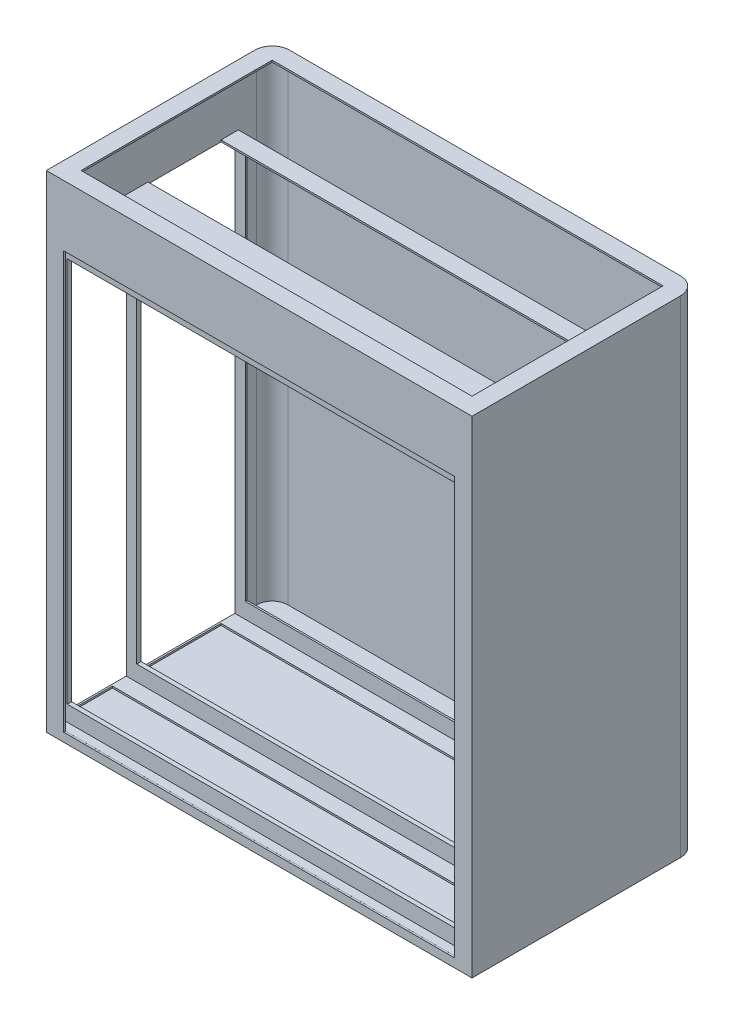
SolidWorks part; units mm, degrees
ref_plane "Front Plane" through (0, 0, 0) normal (0, 0, 1) x (1, 0, 0)
ref_plane "Top Plane" through (0, 0, 0) normal (0, 1, 0) x (1, 0, 0)
ref_plane "Right Plane" through (0, 0, 0) normal (1, 0, 0) x (0, 0, -1)
sketch "Sketch1" plane through (0, 0, 0) normal (0, 1, 0) x (1, 0, 0)
  line L0 (-285.75, 175.26) -> (285.75, 175.26)
  line L1 (-311.15, -152.4) -> (-285.75, -152.4)
  line L2 (-311.15, -152.4) -> (-311.15, 152.4)
  line L3 (-285.75, 177.8) -> (285.75, 177.8)
  line L4 (311.15, -152.4) -> (311.15, 152.4)
  line L5 (-311.15, -177.8) -> (311.15, 177.8) construction
  line L6 (-311.15, 177.8) -> (311.15, -177.8) construction
  line L7 (308.61, -149.86) -> (308.61, 152.4)
  line L8 (-285.75, -152.4) -> (-285.75, -149.86)
  line L9 (-308.61, -149.86) -> (-308.61, 152.4)
  line L10 (-285.75, -149.86) -> (-308.61, -149.86)
  line L11 (311.15, -152.4) -> (285.75, -152.4)
  line L12 (285.75, -152.4) -> (285.75, -149.86)
  line L13 (285.75, -149.86) -> (308.61, -149.86)
  line L14 (-285.75, -177.8) -> (285.75, -177.8) construction
  line L15 (-285.75, -175.26) -> (285.75, -175.26) construction
  line L16 (-308.61, -152.4) -> (-308.61, 152.4) construction
  line L17 (308.61, -152.4) -> (308.61, 152.4) construction
  arc A0 (285.75, -175.26) -> (308.61, -152.4) centre (285.75, -152.4) ccw construction
  arc A2 (285.75, 177.8) -> (311.15, 152.4) centre (285.75, 152.4) cw
  arc A3 (-311.15, 152.4) -> (-285.75, 177.8) centre (-285.75, 152.4) cw
  arc A4 (-308.61, 152.4) -> (-285.75, 175.26) centre (-285.75, 152.4) cw
  arc A5 (285.75, 175.26) -> (308.61, 152.4) centre (285.75, 152.4) cw
  arc A7 (285.75, -177.8) -> (311.15, -152.4) centre (285.75, -152.4) ccw construction
  arc A8 (-285.75, -177.8) -> (-311.15, -152.4) centre (-285.75, -152.4) cw construction
  arc A9 (-285.75, -175.26) -> (-308.61, -152.4) centre (-285.75, -152.4) cw construction
  point P0 (0, 0)
  dimension "D3" = 25.4
  dimension "D1" = 355.6
  dimension "D2" = 622.3
  dimension "D5" = 2.54
  dimension "D6" = 25.4
  dimension "D7" = 2.54
  dimension "D4" = 2.54
extrude "Boss-Extrude1" add sketch "Sketch1" along normal blind 711.2
sketch "Sketch2" plane through (-311.15, 0, 0) normal (-1, 0, 0) x (0, 0, 1)
  line L0 (152.4, 12.7) -> (111.76, 12.7) construction
  line L1 (149.86, 622.3) -> (137.16, 622.3)
  line L2 (-100.33, 12.7) -> (-123.19, 12.7)
  line L3 (149.86, 12.7) -> (137.16, 12.7)
  line L4 (137.16, 622.3) -> (137.16, 599.44)
  line L5 (130.81, 622.3) -> (111.76, 622.3)
  line L6 (130.81, 622.3) -> (130.81, 599.44)
  line L7 (130.81, 12.7) -> (111.76, 12.7)
  line L8 (35.56, 622.3) -> (35.56, 599.44)
  line L9 (29.21, 622.3) -> (6.35, 622.3)
  line L10 (29.21, 622.3) -> (29.21, 599.44)
  line L11 (29.21, 12.7) -> (6.35, 12.7)
  line L12 (-123.19, 622.3) -> (-123.19, 599.44)
  line L13 (152.4, 711.2) -> (152.4, 0) construction
  line L15 (149.86, 0) -> (-152.4, 0) construction
  line L16 (137.16, 10.16) -> (149.86, 10.16)
  line L17 (149.86, 10.16) -> (149.86, 12.7)
  line L18 (-125.73, 599.44) -> (-123.19, 599.44)
  line L19 (-125.73, 624.84) -> (-125.73, 599.44)
  line L20 (-123.19, 317.5) -> (130.81, 317.5) construction
  line L21 (-100.33, 624.84) -> (-125.73, 624.84)
  line L22 (-100.33, 622.3) -> (-100.33, 624.84)
  line L23 (137.16, 10.16) -> (137.16, 12.7)
  line L24 (6.35, 624.84) -> (6.35, 622.3)
  line L25 (58.42, 624.84) -> (6.35, 624.84)
  line L26 (134.0991, 35.56) -> (137.16, 35.56)
  line L27 (134.0991, 35.56) -> (130.81, 35.56)
  line L28 (58.42, 622.3) -> (58.42, 624.84)
  line L29 (29.21, 599.44) -> (35.56, 599.44)
  line L30 (137.16, 10.16) -> (111.76, 10.16)
  line L31 (111.76, 10.16) -> (111.76, 12.7)
  line L32 (58.42, 12.7) -> (58.42, 10.16)
  line L33 (58.42, 10.16) -> (6.35, 10.16)
  line L34 (6.35, 10.16) -> (6.35, 12.7)
  line L35 (-100.33, 12.7) -> (-100.33, 10.16)
  line L36 (29.21, 35.56) -> (35.56, 35.56)
  line L37 (-100.33, 10.16) -> (-125.73, 10.16)
  line L38 (-125.73, 10.16) -> (-125.73, 35.56)
  line L39 (-125.73, 35.56) -> (-123.19, 35.56)
  line L40 (111.76, 624.84) -> (111.76, 622.3)
  line L41 (137.16, 624.84) -> (111.76, 624.84)
  line L42 (137.16, 624.84) -> (149.86, 624.84)
  line L43 (149.86, 624.84) -> (149.86, 622.3)
  line L44 (134.0991, 599.44) -> (137.16, 599.44)
  line L45 (134.0991, 599.44) -> (130.81, 599.44)
  line L46 (-123.19, 35.56) -> (-123.19, 12.7)
  line L47 (-100.33, 622.3) -> (-123.19, 622.3)
  line L48 (29.21, 35.56) -> (29.21, 12.7)
  line L49 (35.56, 35.56) -> (35.56, 12.7)
  line L50 (130.81, 35.56) -> (130.81, 12.7)
  line L51 (137.16, 35.56) -> (137.16, 12.7)
  line L52 (58.42, 622.3) -> (35.56, 622.3)
  line L53 (-100.33, 12.7) -> (-125.73, 12.7) construction
  line L54 (58.42, 12.7) -> (6.35, 12.7) construction
  line L55 (58.42, 12.7) -> (35.56, 12.7)
  point P58 (-91.7591, 55.0071)
  dimension "D4" = 12.7
  dimension "D5" = 95.25
  dimension "D6" = 152.4
  dimension "D7" = 12.7
  dimension "D8" = 6.35
  dimension "D9" = 6.35
  dimension "D11" = 25.4
  dimension "D12" = 2.54
  dimension "D13" = 25.4
  dimension "D14" = 2.54
  dimension "D15" = 22.86
  dimension "D16" = 22.86
  dimension "D17" = 25.4
  dimension "D18" = 25.4
  dimension "D19" = 25.4
  dimension "D20" = 2.54
  dimension "D21" = 2.54
extrude "Boss-Extrude2" add sketch "Sketch2" against normal up to surface (619.76 mm away) contours L47 L22 L21 L19 L18 L12 | L52 L28 L25 L24 L9 L10 L29 L8 | L45 L44 L4 L1 L43 L42 L41 L40 L5 L6 | L46 L39 L38 L37 L35 L2 | L32 L55 L49 L36 L48 L11 L34 L33 | L51 L26 L27 L50 L7 L31 L30 L23 | L23 L16 L17 L3 up to face at (308.61, 355.6, -1.27)
sketch "Sketch3" plane through (-311.15, 0, 0) normal (-1, 0, 0) x (0, 0, 1)
  line L1 (-123.19, 622.3) -> (29.21, 622.3)
  line L2 (-123.19, 622.3) -> (-123.19, 12.7)
  line L3 (-123.19, 12.7) -> (29.21, 12.7)
  line L4 (29.21, 622.3) -> (29.21, 12.7)
  line L5 (35.56, 12.7) -> (130.81, 12.7)
  line L6 (35.56, 12.7) -> (35.56, 622.3)
  line L7 (35.56, 622.3) -> (130.81, 622.3)
  line L8 (130.81, 12.7) -> (130.81, 622.3)
  line L9 (137.16, 622.3) -> (149.86, 622.3)
  line L10 (137.16, 622.3) -> (137.16, 12.7)
  line L11 (137.16, 12.7) -> (149.86, 12.7)
  line L12 (149.86, 622.3) -> (149.86, 12.7)
extrude "Cut-Extrude1" cut sketch "Sketch3" against normal blind 2.54
sketch "Sketch4" plane through (0, 624.84, 0) normal (0, 1, 0) x (1, 0, 0)
  line L0 (-308.61, -29.21) -> (-308.61, -35.56) construction
  line L1 (-308.61, -130.81) -> (-308.61, -137.16) construction
  line L2 (-308.61, 125.73) -> (-308.61, 123.19) construction
  line L3 (-308.61, -29.21) -> (-308.61, -35.56)
  line L4 (-308.61, -130.81) -> (-308.61, -137.16)
  line L5 (-308.61, 125.73) -> (-308.61, 123.19)
  line L6 (-308.61, 123.19) -> (-295.91, 123.19)
  line L7 (-295.91, 123.19) -> (-295.91, 125.73)
  line L8 (308.61, 125.73) -> (-308.61, 125.73) construction
  line L9 (-295.91, 125.73) -> (-308.61, 125.73)
  line L10 (-308.61, -29.21) -> (-295.91, -29.21)
  line L11 (-295.91, -29.21) -> (-295.91, -35.56)
  line L12 (-295.91, -35.56) -> (-308.61, -35.56)
  line L13 (-308.61, -130.81) -> (-295.91, -130.81)
  line L14 (-295.91, -130.81) -> (-295.91, -137.16)
  line L15 (-295.91, -137.16) -> (-308.61, -137.16)
  line L16 (0, 0) -> (0, 245.9045) construction
  line L17 (295.91, -137.16) -> (308.61, -137.16)
  line L18 (295.91, -130.81) -> (295.91, -137.16)
  line L19 (308.61, -130.81) -> (295.91, -130.81)
  line L20 (295.91, -35.56) -> (308.61, -35.56)
  line L21 (295.91, -29.21) -> (295.91, -35.56)
  line L22 (308.61, -29.21) -> (295.91, -29.21)
  line L23 (295.91, 125.73) -> (308.61, 125.73)
  line L24 (295.91, 123.19) -> (295.91, 125.73)
  line L25 (308.61, 123.19) -> (295.91, 123.19)
  line L26 (308.61, 125.73) -> (308.61, 123.19)
  line L27 (308.61, -130.81) -> (308.61, -137.16)
  line L28 (308.61, -29.21) -> (308.61, -35.56)
  dimension "D1" = 12.7
  dimension "D2" = 12.7
  dimension "D3" = 12.7
extrude "Boss-Extrude3" add sketch "Sketch4" against normal up to surface (589.28 mm away) up to face at (0, 35.56, 32.385)
sketch "Sketch5" plane through (0, 0, 152.4) normal (0, 0, 1) x (1, 0, 0)
  line L0 (285.75, 711.2) -> (285.75, 0) construction
  line L1 (-285.75, 0) -> (285.75, 0)
  line L2 (-285.75, 0) -> (-285.75, 12.6682)
  line L3 (-285.75, 12.6682) -> (285.75, 12.6682)
  line L4 (285.75, 0) -> (285.75, 12.6682)
extrude "Boss-Extrude4" add sketch "Sketch5" against normal blind 2.54
sketch "Sketch6" plane through (0, 711.2, 0) normal (0, 1, 0) x (1, 0, 0)
  line L0 (-285.75, -124.46) -> (-285.75, -152.4)
  line L1 (285.75, -127) -> (285.75, -127)
  line L2 (285.75, -127) -> (285.75, 152.4)
  line L3 (285.75, 152.4) -> (-285.75, 152.4)
  line L4 (-285.75, 152.4) -> (-285.75, -124.46)
  line L5 (-285.75, -124.46) -> (-285.75, -124.46)
  line L6 (-285.75, -124.46) -> (-285.75, -124.46)
  line L7 (285.75, -152.4) -> (285.75, -127)
  line L9 (-285.75, -152.4) -> (-285.75, -149.86) construction
  line L12 (-311.15, 152.4) -> (-311.15, -152.4)
  line L13 (-311.15, -152.4) -> (-285.75, -152.4)
  line L14 (-285.75, -152.4) -> (-285.75, -149.86)
  line L15 (-285.75, -149.86) -> (-308.61, -149.86)
  line L16 (-308.61, -149.86) -> (-308.61, 152.4)
  line L17 (-285.75, 175.26) -> (285.75, 175.26)
  line L18 (308.61, 152.4) -> (308.61, -149.86)
  line L19 (308.61, -149.86) -> (285.75, -149.86)
  line L20 (285.75, -149.86) -> (285.75, -152.4)
  line L21 (285.75, -152.4) -> (311.15, -152.4)
  line L22 (311.15, -152.4) -> (311.15, 152.4)
  line L23 (285.75, 177.8) -> (-285.75, 177.8)
  line L24 (-311.15, 152.4) -> (-311.15, -152.4)
  line L25 (-311.15, -152.4) -> (-285.75, -152.4)
  line L33 (285.75, -152.4) -> (311.15, -152.4)
  line L34 (311.15, -152.4) -> (311.15, 152.4)
  line L35 (285.75, 177.8) -> (-285.75, 177.8)
  arc A0 (285.75, 152.4) -> (285.75, 152.4) centre (285.75, 152.4) ccw
  arc A1 (-285.75, 152.4) -> (-285.75, 152.4) centre (-285.75, 152.4) ccw
  arc A4 (-285.75, 175.26) -> (-308.61, 152.4) centre (-285.75, 152.4) ccw
  arc A5 (308.61, 152.4) -> (285.75, 175.26) centre (285.75, 152.4) ccw
  arc A6 (311.15, 152.4) -> (285.75, 177.8) centre (285.75, 152.4) ccw
  arc A7 (-285.75, 177.8) -> (-311.15, 152.4) centre (-285.75, 152.4) ccw
  arc A10 (311.15, 152.4) -> (285.75, 177.8) centre (285.75, 152.4) ccw
  arc A11 (-285.75, 177.8) -> (-311.15, 152.4) centre (-285.75, 152.4) ccw
  line M20 (-285.75, -149.86) -> (-308.61, -149.86)
  line M21 (-308.61, -149.86) -> (-308.61, 152.4)
  arc M22 (-308.61, 152.4) -> (-285.75, 175.26) centre (-285.75, 152.4) cw
  line M23 (-285.75, 175.26) -> (285.75, 175.26)
  arc M24 (285.75, 175.26) -> (308.61, 152.4) centre (285.75, 152.4) cw
  line M25 (308.61, 152.4) -> (308.61, -149.86)
  line M26 (308.61, -149.86) -> (285.75, -149.86)
  dimension "D1" = 0
  dimension "D2" = 25.4
extrude "Boss-Extrude5" add sketch "Sketch6" against normal blind 2.54 contours L7 L0 L4 L3 L2 M26 M25 M24 M23 M22 M21 M20
sketch "Sketch7" plane through (0, 0, 149.86) normal (0, 0, 1) x (1, 0, 0)
  line L1 (-285.75, 641.35) -> (285.75, 641.35)
  line L4 (285.75, 624.84) -> (-285.75, 624.84)
  line L5 (-285.75, 624.84) -> (-285.75, 622.3)
  line L6 (-285.75, 622.3) -> (285.75, 622.3)
  line L7 (285.75, 622.3) -> (285.75, 624.84)
  line L9 (-285.75, 641.35) -> (-285.75, 622.3)
  line L10 (-285.75, 622.3) -> (285.75, 622.3)
  line L11 (285.75, 622.3) -> (285.75, 641.35)
  dimension "D2" = 19.05
  dimension "D1" = 0
extrude "Boss-Extrude6" add sketch "Sketch7" along normal up to surface (2.54 mm away) up to face at (0, 358.767, 152.4)
sketch "Sketch9" plane through (0, 641.35, 0) normal (0, 1, 0) x (1, 0, 0)
  line L4 (-285.75, -149.86) -> (-285.75, -152.4)
  line L5 (-285.75, -152.4) -> (285.75, -152.4)
  line L6 (285.75, -152.4) -> (285.75, -149.86)
  line L7 (285.75, -149.86) -> (-285.75, -149.86)
  line L8 (-285.75, -149.86) -> (-285.75, -152.4)
  line L9 (-285.75, -152.4) -> (285.75, -152.4)
  line L10 (285.75, -152.4) -> (285.75, -149.86)
  line L11 (285.75, -149.86) -> (-285.75, -149.86)
  dimension "D1" = 0
extrude "Boss-Extrude7" add sketch "Sketch9" along normal up to surface (69.85 mm away) up to face at (0, 711.2, -36.6121)
sketch "Sketch10" plane through (0, 711.2, 0) normal (0, 1, 0) x (1, 0, 0)
  line L0 (-285.75, -149.86) -> (-285.75, 152.4) construction
  line L1 (285.75, -149.86) -> (-285.75, -149.86)
  line L2 (285.75, -149.86) -> (285.75, -127)
  line L3 (285.75, -127) -> (-285.75, -127)
  line L4 (-285.75, -149.86) -> (-285.75, -127)
  dimension "D1" = 22.86
extrude "Boss-Extrude8" add sketch "Sketch10" against normal blind 2.54
sketch "Sketch11" plane through (0, 10.16, 0) normal (0, -1, 0) x (1, 0, 0)
  line L0 (-308.61, 149.86) -> (-308.61, -152.4) construction
  line L1 (-285.75, -175.26) -> (285.75, -175.26) construction
  line L2 (308.61, -152.4) -> (308.61, 149.86) construction
  line L3 (308.61, 149.86) -> (-308.61, 149.86) construction
  line L4 (-308.61, 149.86) -> (-308.61, -152.4)
  line L5 (-285.75, -175.26) -> (285.75, -175.26)
  line L6 (308.61, -152.4) -> (308.61, 149.86)
  line L7 (308.61, 149.86) -> (-308.61, 149.86)
  arc A0 (-308.61, -152.4) -> (-285.75, -175.26) centre (-285.75, -152.4) ccw construction
  arc A1 (285.75, -175.26) -> (308.61, -152.4) centre (285.75, -152.4) ccw construction
  arc A2 (-308.61, -152.4) -> (-285.75, -175.26) centre (-285.75, -152.4) ccw
  arc A3 (285.75, -175.26) -> (308.61, -152.4) centre (285.75, -152.4) ccw
extrude "Boss-Extrude9" add sketch "Sketch11" along normal up to surface (10.16 mm away) up to face at (0, 0, -60.8448)
